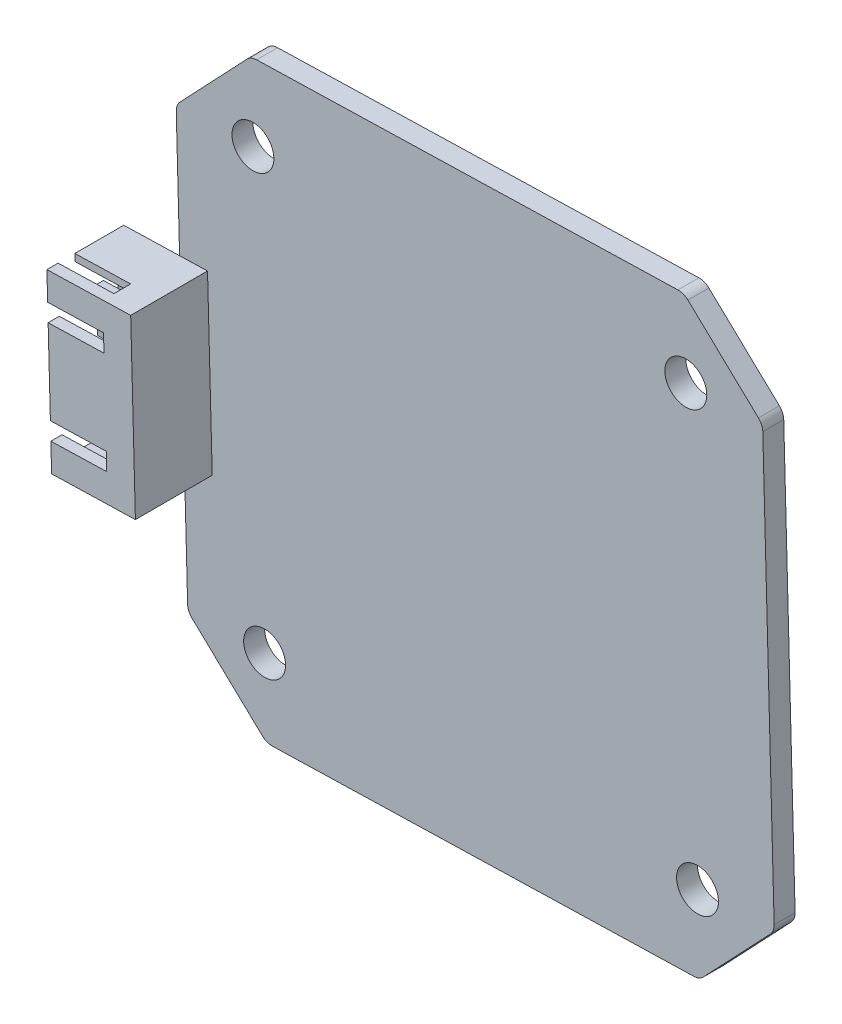
SolidWorks part; units mm, degrees
ref_plane "前视基准面" through (0, 0, 0) normal (0, 0, 1) x (1, 0, 0)
ref_plane "上视基准面" through (0, 0, 0) normal (0, 1, 0) x (1, 0, 0)
ref_plane "右视基准面" through (0, 0, 0) normal (1, 0, 0) x (0, 0, -1)
sketch "草图1" plane through (0, 0, 0) normal (0, 0, 1) x (1, 0, 0)
  line L0 (-36.2845, -8.4813) -> (-35.8532, -24.4755)
  line L24 (-35.8532, -24.4755) -> (-35.6621, -31.5587)
  line L25 (-35.3503, -32.2577) -> (-30.3053, -37.0376)
  line L26 (-29.5906, -37.3113) -> (0.57, -36.4979)
  line L27 (1.269, -36.186) -> (6.0489, -31.1411)
  line L28 (6.3226, -30.4264) -> (5.5092, -0.2658)
  line L29 (5.1973, 0.4332) -> (0.1524, 5.2131)
  line L30 (-0.5623, 5.4868) -> (-30.723, 4.6734)
  line L31 (-31.4219, 4.3615) -> (-36.2018, -0.6834)
  line L32 (-36.4756, -1.3981) -> (-36.2845, -8.4813)
  circle A0 centre (-30.9887, -0.8358) radius 1.5
  circle A1 centre (0, 0) radius 1.5
  circle A2 centre (0.8358, -30.9887) radius 1.5
  circle A3 centre (-30.1529, -31.8245) radius 1.5
  arc A16 (-35.6621, -31.5587) -> (-35.3503, -32.2577) centre (-34.6625, -31.5318) ccw
  arc A17 (-30.3053, -37.0376) -> (-29.5906, -37.3113) centre (-29.6176, -36.3117) ccw
  arc A18 (0.57, -36.4979) -> (1.269, -36.186) centre (0.543, -35.4983) ccw
  arc A19 (6.0489, -31.1411) -> (6.3226, -30.4264) centre (5.323, -30.4533) ccw
  arc A20 (5.5092, -0.2658) -> (5.1973, 0.4332) centre (4.5095, -0.2927) ccw
  arc A21 (0.1524, 5.2131) -> (-0.5623, 5.4868) centre (-0.5354, 4.4872) ccw
  arc A22 (-30.723, 4.6734) -> (-31.4219, 4.3615) centre (-30.696, 3.6737) ccw
  arc A23 (-36.2018, -0.6834) -> (-36.4756, -1.3981) centre (-35.4759, -1.3712) ccw
extrude "凸台-拉伸1" add sketch "草图1" along normal blind 1.5
sketch "草图2" plane through (-36.4867, -0.9841, 0) normal (-0.9996, -0.027, 0) x (0, 0, 1)
  line L0 (1.5, -0.4142) -> (1.5, -30.5858) construction
  line L1 (1.5, -9.25) -> (7, -9.25)
  line L2 (1.5, -9.25) -> (1.5, -21.75)
  line L3 (1.5, -21.75) -> (7, -21.75)
  line L4 (7, -9.25) -> (7, -21.75)
  line L5 (1.5, -9.25) -> (7, -21.75) construction
  line L6 (1.5, -21.75) -> (7, -9.25) construction
  line L7 (1.5, -15.5) -> (8.0228, -15.5) construction
  point P4 (4.25, -15.5)
  dimension "D1" = 12.5
  dimension "D2" = 5.5
extrude "凸台-拉伸2" add sketch "草图2" against normal blind 2
sketch "草图3" plane through (-36.4867, -0.9841, 0) normal (-0.9996, -0.027, 0) x (0, 0, 1)
  line L0 (7, -15.5) -> (0, -15.5) construction
  line L1 (7, -21.75) -> (7, -9.25) construction
  line L2 (0, -0.4142) -> (0, -30.5858) construction
  line L3 (5, -21.75) -> (5, -21.25)
  line L4 (1.5, -21.75) -> (7, -21.75) construction
  line L5 (5, -21.25) -> (2, -21.25)
  line L6 (2, -21.25) -> (2, -9.75)
  line L7 (6.2, -21.75) -> (6.2, -19.75)
  line L8 (6.2, -19.75) -> (7, -19.75)
  line L9 (6.2, -21.75) -> (7, -21.75)
  line L10 (7, -21.75) -> (7, -19.75)
  line L11 (7, -18.5) -> (6.2, -18.5)
  line L12 (6.2, -18.5) -> (6.2, -12.5)
  line L13 (1.5, -21.75) -> (1.5, -30.5858) construction
  line L14 (7, -12.5) -> (6.2, -12.5)
  line L15 (7, -9.25) -> (7, -11.25)
  line L16 (6.2, -9.25) -> (7, -9.25)
  line L17 (6.2, -11.25) -> (7, -11.25)
  line L18 (6.2, -9.25) -> (6.2, -11.25)
  line L19 (5, -9.75) -> (2, -9.75)
  line L20 (5, -9.25) -> (5, -9.75)
  line L21 (5, -21.75) -> (1.5, -21.75)
  line L22 (1.5, -21.75) -> (1.5, -9.25)
  line L23 (1.5, -9.25) -> (5, -9.25)
  point P22 (6.2, -15.5)
  point P28 (2, -15.5)
  line M11 (1.5, -21.75) -> (7, -21.75)
  line M12 (7, -21.75) -> (7, -9.25)
  line M13 (7, -9.25) -> (1.5, -9.25)
  dimension "D1" = 0.5
  dimension "D2" = 2
  dimension "D3" = 0.8
  dimension "D4" = 0.5
  dimension "D5" = 0.8
  dimension "D6" = 3
  dimension "D7" = 3
extrude "凸台-拉伸3" add sketch "草图3" along normal blind 4 contours L6 L0 L22 L3 L5 M11 | L0 L6 L19 L20 L22 M13 | L8 L7 M11 M12 | L0 L12 L11 M12 | L0 L14 L12 M12 | L18 L17 M13 M12
sketch "草图4" plane through (-36.4867, -0.9841, 0) normal (-0.9996, -0.027, 0) x (0, 0, 1)
  line L0 (1.5, -15.5) -> (7, -15.5) construction
  line L1 (1.5, -21.75) -> (1.5, -9.25) construction
  line L2 (7, -18.5) -> (7, -12.5) construction
  line L3 (4.25, -15.5) -> (4.25, -21.0701) construction
  line L4 (4.5, -20.0721) -> (4, -20.0721)
  line L5 (4.5, -20.0721) -> (4.5, -19.5721)
  line L6 (4.5, -19.5721) -> (4, -19.5721)
  line L7 (4, -20.0721) -> (4, -19.5721)
  line L8 (4.5, -20.0721) -> (4, -19.5721) construction
  line L9 (4.5, -19.5721) -> (4, -20.0721) construction
  line L10 (4.5, -17.4483) -> (4, -17.4483)
  line L11 (4.5, -17.4483) -> (4.5, -16.9483)
  line L12 (4.5, -16.9483) -> (4, -16.9483)
  line L13 (4, -17.4483) -> (4, -16.9483)
  line L14 (4.5, -17.4483) -> (4, -16.9483) construction
  line L15 (4.5, -16.9483) -> (4, -17.4483) construction
  line L16 (4.5, -14.0517) -> (4, -13.5517) construction
  line L17 (4.5, -13.5517) -> (4, -14.0517) construction
  line L18 (4.5, -11.4279) -> (4, -10.9279) construction
  line L19 (4.5, -10.9279) -> (4, -11.4279) construction
  line L20 (4, -13.5517) -> (4, -14.0517)
  line L21 (4.5, -14.0517) -> (4, -14.0517)
  line L22 (4.5, -13.5517) -> (4.5, -14.0517)
  line L23 (4.5, -13.5517) -> (4, -13.5517)
  line L24 (4, -10.9279) -> (4, -11.4279)
  line L25 (4.5, -11.4279) -> (4, -11.4279)
  line L26 (4.5, -10.9279) -> (4.5, -11.4279)
  line L27 (4.5, -10.9279) -> (4, -10.9279)
  point P10 (4.25, -19.8221)
  point P18 (4.25, -17.1983)
  point P26 (4.25, -13.8017)
  point P27 (4.25, -11.1779)
  point P28 (4.25, -17.4462)
  point P29 (4.25, -17.1983)
  dimension "D1" = 0.5
  dimension "D2" = 0.5
  dimension "D3" = 0.5
  dimension "D4" = 0.5
extrude "凸台-拉伸4" add sketch "草图4" along normal blind 3
